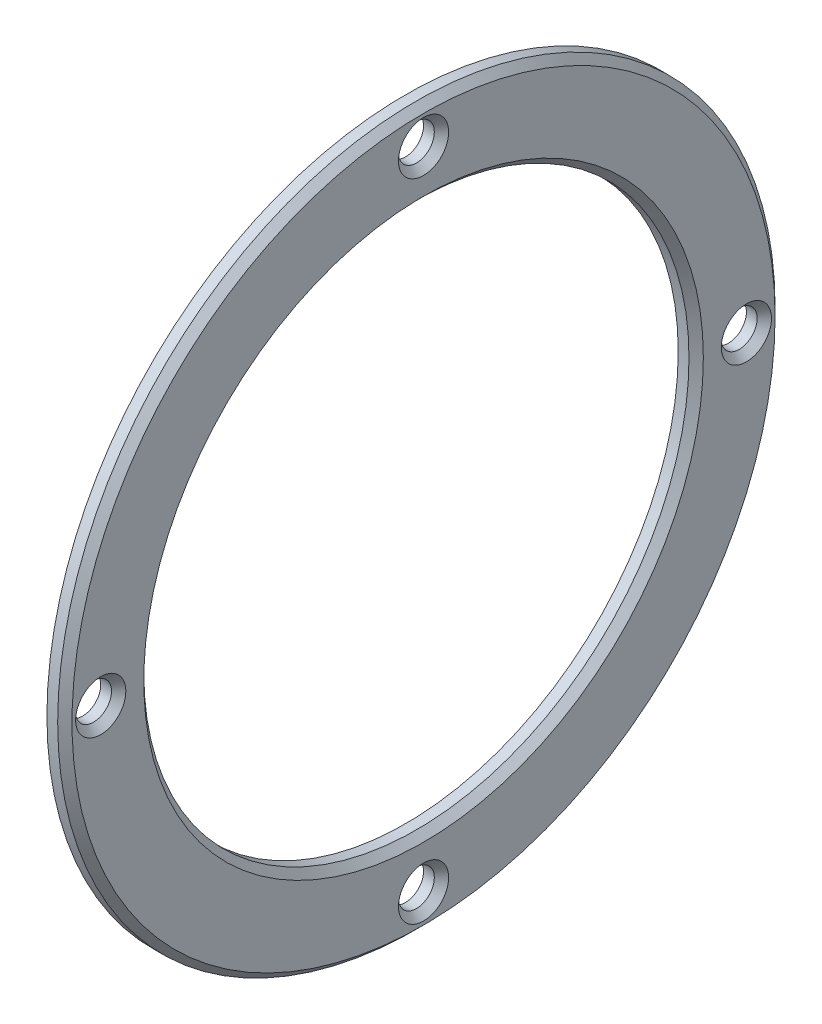
SolidWorks part; units mm, degrees
ref_plane "Front Plane" through (0, 0, 0) normal (0, 0, 1) x (1, 0, 0)
ref_plane "Top Plane" through (0, 0, 0) normal (0, 1, 0) x (1, 0, 0)
ref_plane "Right Plane" through (0, 0, 0) normal (1, 0, 0) x (0, 0, -1)
sketch "Sketch1" plane through (0, 0, 0) normal (1, 0, 0) x (0, 0, -1)
  circle A0 centre (0, 0) radius 38
  circle A1 centre (0, 0) radius 50
  circle A2 centre (0, 0) radius 45 construction
  circle A3 centre (0, 45) radius 2.5
  circle A4 centre (45, 0) radius 2.5
  circle A5 centre (0, -45) radius 2.5
  circle A6 centre (-45, 0) radius 2.5
  point P7 (-5.0329, 0)
  point P8 (0, 0)
  point P16 (0, 0)
  dimension "D1" = 76
  dimension "D2" = 100
  dimension "D3" = 90
  dimension "D4" = 5
  dimension "D5" = 4
extrude "Boss-Extrude1" add sketch "Sketch1" along normal blind 2.5
chamfer "Chamfer1" distance 1 angle 45 6 edges at (2.5, 0, 42.5) (2.5, 0, -47.5) (2.5, 0, -38) (2.5, 0, -50) (2.5, 45, -2.5) (2.5, -45, -2.5)
